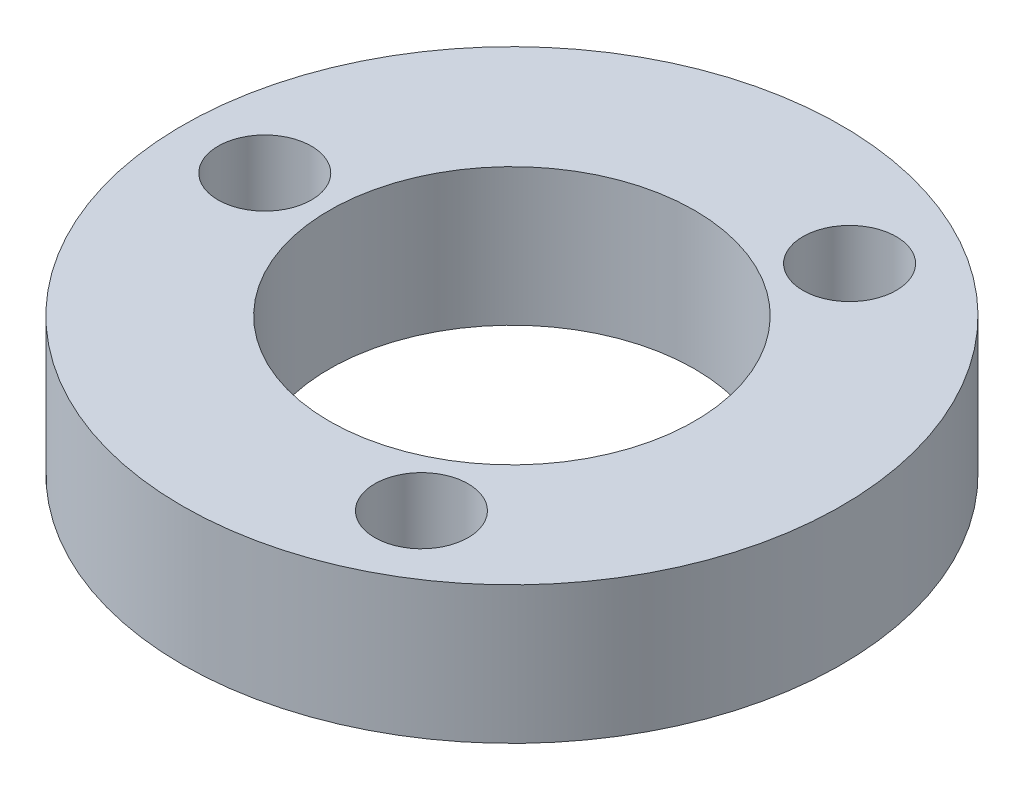
SolidWorks part; units mm, degrees
ref_plane "Спереди" through (0, 0, 0) normal (0, 0, 1) x (1, 0, 0)
ref_plane "Сверху" through (0, 0, 0) normal (0, 1, 0) x (1, 0, 0)
ref_plane "Справа" through (0, 0, 0) normal (1, 0, 0) x (0, 0, -1)
sketch "Эскиз1" plane through (0, 0, 0) normal (0, 1, 0) x (1, 0, 0)
  line L0 (0, 0) -> (-14.0959, 0) construction
  line L1 (0, 0) -> (8.6852, 15.0432) construction
  line L2 (0, 0) -> (9.7771, -16.9344) construction
  circle A0 centre (0, 0) radius 12
  circle A1 centre (0, 0) radius 6.65
  circle A2 centre (0, 0) radius 9 construction
  circle A3 centre (0, 0) radius 10.7 construction
  circle A4 centre (-9, 0) radius 1.7
  circle A5 centre (4.5, 7.7942) radius 1.7
  circle A6 centre (4.5, -7.7942) radius 1.7
  dimension "D1" = 13.3
  dimension "D2" = 24
  dimension "D3" = 18
  dimension "D4" = 21.4
  dimension "D5" = 120
  dimension "D6" = 120
extrude "Бобышка-Вытянуть1" add sketch "Эскиз1" along normal blind 5
